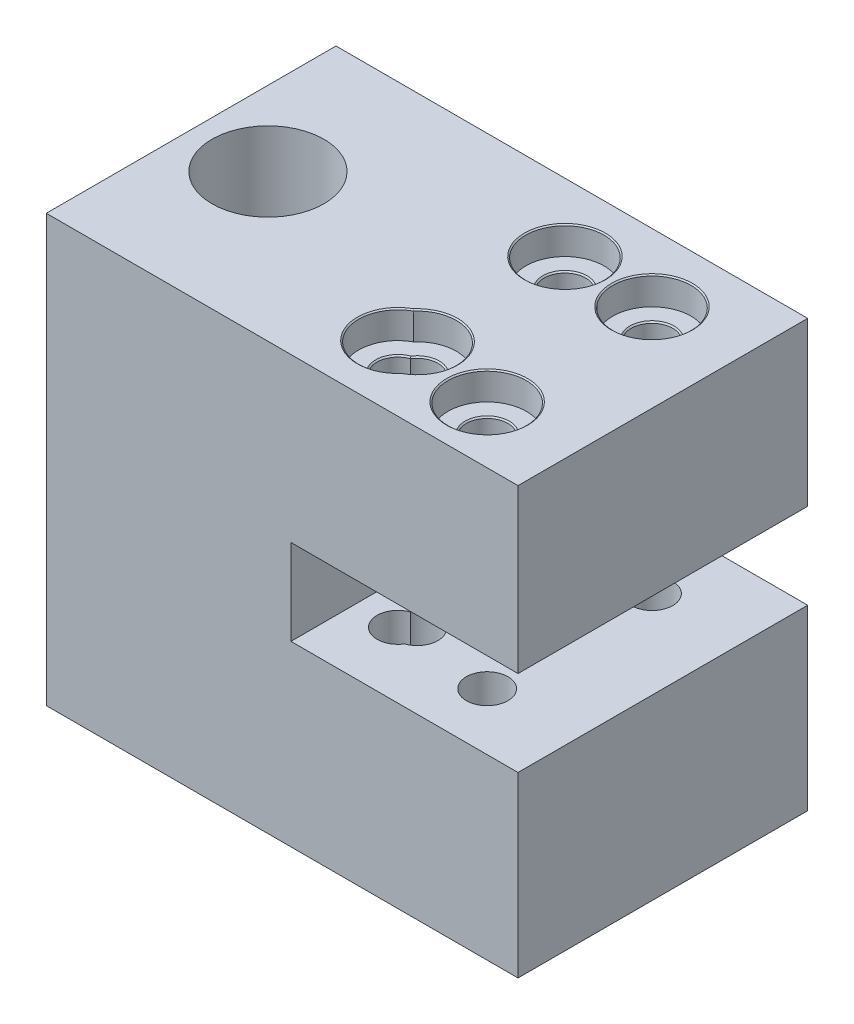
SolidWorks part; units mm, degrees
ref_plane "Front Plane" through (0, 0, 0) normal (0, 0, 1) x (1, 0, 0)
ref_plane "Top Plane" through (0, 0, 0) normal (0, 1, 0) x (1, 0, 0)
ref_plane "Right Plane" through (0, 0, 0) normal (1, 0, 0) x (0, 0, -1)
sketch "Sketch1" plane through (0, 0, 0) normal (0, 1, 0) x (1, 0, 0)
  line L1 (-124.608, 68.005) -> (100.175, 68.005)
  line L2 (-124.608, 68.005) -> (-124.608, -70.0411)
  line L3 (-124.608, -70.0411) -> (100.175, -70.0411)
  line L4 (100.175, 68.005) -> (100.175, -70.0411)
extrude "Boss-Extrude1" add sketch "Sketch1" along normal mid plane 203.2 contours L2 L1 L4 L3
sketch "Sketch2" plane through (0, 101.6, 0) normal (0, 1, 0) x (1, 0, 0)
  circle A0 centre (-89.0236, 0) radius 26.6682
extrude "Cut-Extrude1" cut sketch "Sketch2" against normal blind 108.204 contours A0
sketch "Sketch4" plane through (100.175, 0, 0) normal (1, 0, 0) x (0, 0, -1)
  line L0 (-70.0411, 101.6) -> (-70.0411, -101.6) construction
  line L1 (-70.0411, 24.0369) -> (68.005, 24.0369)
  line L2 (-70.0411, 24.0369) -> (-70.0411, -16.7805)
  line L3 (-70.0411, -16.7805) -> (68.005, -16.7805)
  line L4 (68.005, 24.0369) -> (68.005, -16.7805)
  line L5 (68.005, 101.6) -> (68.005, -101.6) construction
extrude "Cut-Extrude2" cut sketch "Sketch4" against normal blind 108.204
hole_wizard "CBORE for 3/4 Pan Head Machine Screw1" positions "Sketch5" profile "Sketch7" counterbore size "3/4" standard "ANSI Inch" end condition through all
sketch "Sketch5" plane through (0, 101.6, 0) normal (0, 1, 0) x (1, 0, 0)
  point P0 (58.2593, -42.8221)
  point P5 (58.2593, 35.7078)
  point P7 (16.7764, 35.7078)
  point P9 (11.6623, -38.7763)
  point P11 (16.7764, -34.6916)
sketch "Sketch7" plane through (58.2593, 101.6, 42.8221) normal (1, 0, 0) x (0, 0, 1)
  line L0 (0, 0) -> (0, 203.2)
  line L1 (0, 203.2) -> (9.9212, 203.2)
  line L3 (9.9212, 13.8684) -> (10.5562, 13.2334)
  line L4 (10.5562, 13.2334) -> (18.6538, 13.2334)
  line L5 (18.6538, 13.2334) -> (18.6538, 0.5328)
  line L6 (18.6538, 0.5328) -> (19.2888, 0)
  line L7 (19.2888, 0) -> (0, 0)
  line L8 (-18.6538, 0.5328) -> (-19.2888, 0) construction
  line L9 (-9.9212, 13.8684) -> (-10.5562, 13.2334) construction
  line L10 (9.9212, 203.2) -> (9.9212, 13.8684)
  line L11 (0, -6.35) -> (0, 107.95) construction
  dimension "Thru Hole Dia." = 19.8425
  dimension "Thru Hole Depth" = 203.2
  dimension "C'Bore Dia." = 37.3075
  dimension "C'Bore Depth" = 13.2334
  dimension "Near C'Sink Dia." = 38.5775
  dimension "Near C'Sink Angle" = 100
  dimension "Mid C'Sink Dia." = 21.1125
  dimension "Mid C'Sink Angle" = 90
